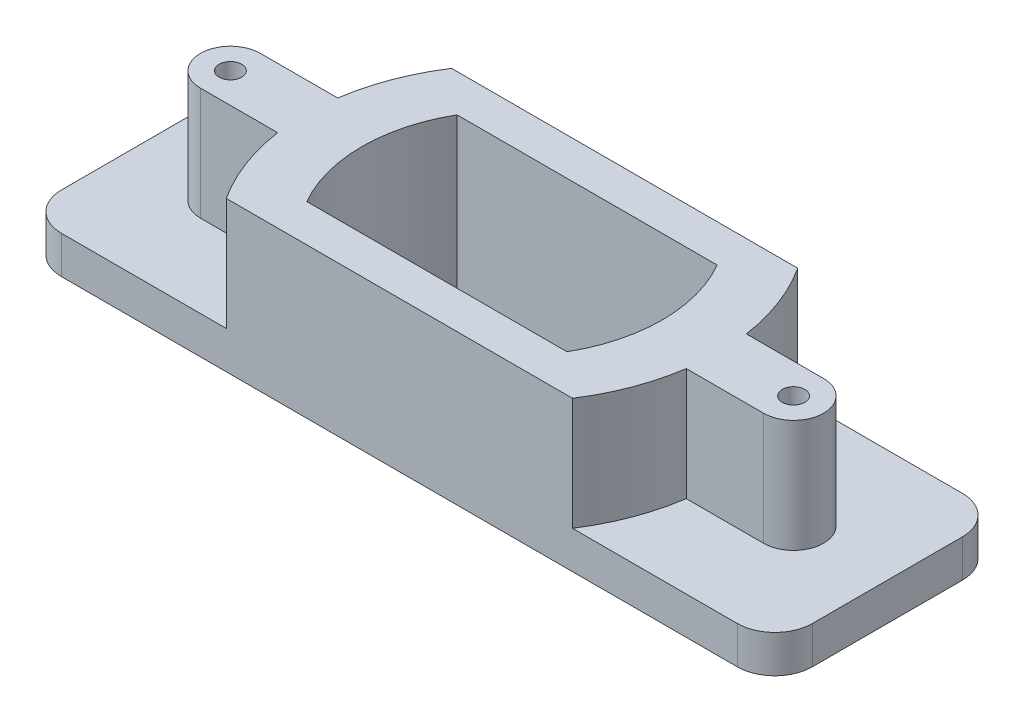
SolidWorks part; units mm, degrees
ref_plane "前视基准面" through (0, 0, 0) normal (0, 0, 1) x (1, 0, 0)
ref_plane "上视基准面" through (0, 0, 0) normal (0, 1, 0) x (1, 0, 0)
ref_plane "右视基准面" through (0, 0, 0) normal (1, 0, 0) x (0, 0, -1)
other "Configuration Table"
sketch "草图1" plane through (0, 0, 0) normal (0, 1, 0) x (1, 0, 0)
  line L0 (100, -20) -> (100, 20)
  line L1 (-90, -30) -> (90, -30)
  line L3 (-100, -20) -> (-100, 20)
  line L4 (-90, 30) -> (90, 30)
  line L6 (0, 30) -> (0, -35) construction
  line L7 (-100, 0) -> (100, 0) construction
  arc A0 (-90, 30) -> (-100, 20) centre (-90, 20) ccw
  arc A1 (90, 30) -> (100, 20) centre (90, 20) cw
  arc A2 (90, -30) -> (100, -20) centre (90, -20) ccw
  arc A3 (-90, -30) -> (-100, -20) centre (-90, -20) cw
  point P1 (0, 0)
  point P2 (189.7814, 69.6997)
  point P7 (201.6486, 70.5762)
  point P15 (0, 0)
  dimension "D1" = 10
  dimension "D2" = 60
  dimension "D3" = 200
extrude "凸台-拉伸2" add sketch "草图1" along normal blind 10 contours L4 A1 L0 A2 L1 A3 L3 A0
sketch "草图5" plane through (0, 10, 0) normal (0, 1, 0) x (1, 0, 0)
  line L0 (0, 0) -> (0, 50000) construction
  line L2 (-90, 30) -> (90, 30) construction
  line L5 (-46.0977, 30) -> (46.0977, 30)
  line L6 (0, 0) -> (-50000, 0) construction
  line L7 (0, 0) -> (-75, 0) construction
  line L8 (-75, 8) -> (-54.4151, 8)
  line L9 (0, 0) -> (0, 25) construction
  line L11 (75, 8) -> (54.4151, 8)
  line L13 (75, -8) -> (54.4151, -8)
  line L14 (-46.0977, -30) -> (46.0977, -30)
  line L15 (-75, -8) -> (-54.4151, -8)
  arc A0 (-46.0977, 30) -> (-54.4151, 8) centre (0, 0) ccw
  arc A2 (-75, -8) -> (-75, 8) centre (-75, 0) cw
  arc A7 (46.0977, 30) -> (54.4151, 8) centre (0, 0) cw
  arc A9 (75, -8) -> (75, 8) centre (75, 0) ccw
  arc A10 (46.0977, -30) -> (54.4151, -8) centre (0, 0) ccw
  arc A11 (-46.0977, -30) -> (-54.4151, -8) centre (0, 0) cw
  point P4 (0, 0)
  point P22 (0, 30)
  dimension "D1" = 55
  dimension "D2" = 75
  dimension "D3" = 8
extrude "凸台-拉伸3" add sketch "草图5" along normal blind 30
sketch "草图7" plane through (0, 0, 0) normal (0, -1, 0) x (1, 0, 0)
  line L0 (0, 0) -> (50000, 0) construction
  line L1 (0, 0) -> (0, -50000) construction
  line L2 (0, 0) -> (0, -20) construction
  line L3 (34.641, -20) -> (-34.641, -20)
  line L4 (0, 0) -> (-75, 0) construction
  line L5 (34.641, 20) -> (-34.641, 20)
  arc A0 (-34.641, 20) -> (-34.641, -20) centre (0, 0) ccw
  circle A1 centre (-75, 0) radius 3
  arc A2 (34.641, 20) -> (34.641, -20) centre (0, 0) cw
  circle A3 centre (75, 0) radius 3
  point P13 (0, 20)
  dimension "D1" = 6
  dimension "D3" = 40
  dimension "D2" = 40
  dimension "D4" = 75
extrude "切除-拉伸3" cut sketch "草图7" against normal up to surface (40 mm away) up to face at (0, 40, 0)
